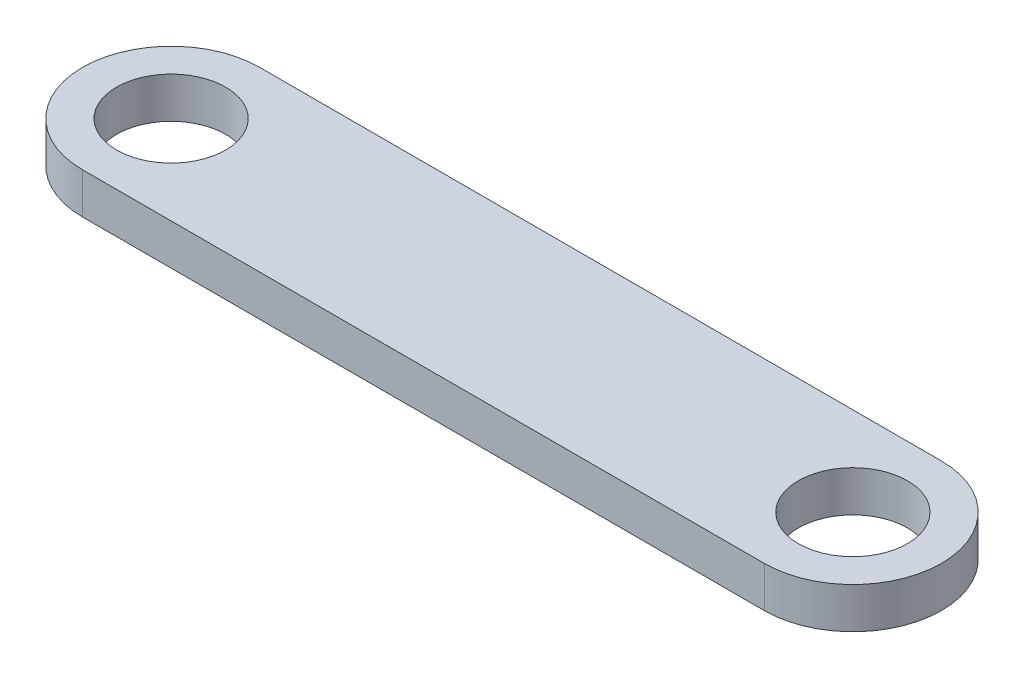
SolidWorks part; units mm, degrees
ref_plane "Front Plane" through (0, 0, 0) normal (0, 0, 1) x (1, 0, 0)
ref_plane "Top Plane" through (0, 0, 0) normal (0, 1, 0) x (1, 0, 0)
ref_plane "Right Plane" through (0, 0, 0) normal (1, 0, 0) x (0, 0, -1)
sketch "Sketch1" plane through (0, 0, 0) normal (0, 1, 0) x (1, 0, 0)
  line L0 (-25, 0) -> (25, 0) construction
  line L1 (-25, 6.5) -> (25, 6.5)
  line L2 (-25, -6.5) -> (25, -6.5)
  arc A0 (-25, 6.5) -> (-25, -6.5) centre (-25, 0) ccw
  arc A1 (25, -6.5) -> (25, 6.5) centre (25, 0) ccw
  circle A2 centre (-25, 0) radius 4
  circle A3 centre (25, 0) radius 4
  point P2 (0, 0)
  dimension "D1" = 8
  dimension "D2" = 50
  dimension "D3" = 2.5
extrude "Boss-Extrude1" add sketch "Sketch1" along normal blind 3
